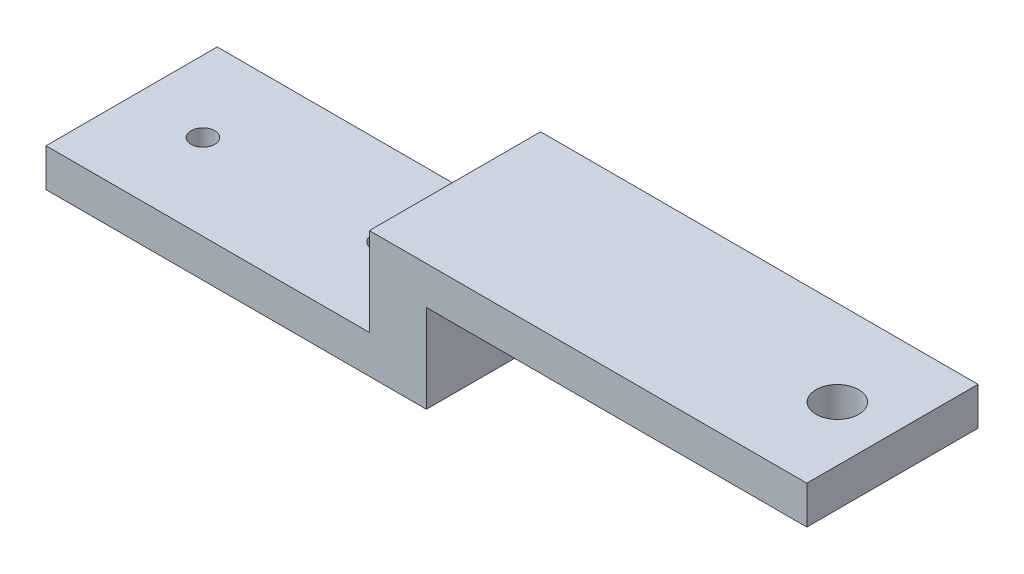
SolidWorks part; units mm, degrees
material "1060 Alloy"
ref_plane "Front Plane" through (0, 0, 0) normal (0, 0, 1) x (1, 0, 0)
ref_plane "Top Plane" through (0, 0, 0) normal (0, 1, 0) x (1, 0, 0)
ref_plane "Right Plane" through (0, 0, 0) normal (1, 0, 0) x (0, 0, -1)
sketch "Sketch1" plane through (0, 0, 0) normal (0, 0, 1) x (1, 0, 0)
  line L0 (-123.8145, -26.5468) -> (-43.8145, -26.5468)
  line L1 (-43.8145, -26.5468) -> (-43.8145, -15.6889)
  line L3 (-29.6039, -8) -> (0.4965, -8)
  line L4 (0.4965, -8) -> (36.1855, -8)
  line L5 (36.1855, -8) -> (36.1855, 0)
  line L6 (36.1855, 0) -> (-33.1894, 0)
  line L9 (-123.8145, -18.5468) -> (-123.8145, -26.5468)
  line L10 (-43.8145, -15.6889) -> (-43.8145, -8)
  line L11 (-43.8145, -8) -> (-29.6039, -8)
  line L14 (-55.8145, 0) -> (-33.1894, 0)
  line L17 (-123.8145, -18.5468) -> (-55.8145, -18.5468)
  line L18 (-55.8145, 0) -> (-55.8145, -18.5468)
  dimension "D1" = 80
  dimension "D2" = 8
  dimension "D3" = 80
  dimension "D4" = 8
  dimension "D5" = 12
  dimension "D6" = 10.5468
extrude "Boss-Extrude1" add sketch "Sketch1" along normal blind 36
sketch "Sketch2" plane through (0, 0, 0) normal (0, 1, 0) x (1, 0, 0)
  line L0 (36.1855, 0) -> (13.0373, -36) construction
  line L1 (36.1855, -36) -> (-55.8145, -36) construction
  line L2 (13.0373, -36) -> (36.1855, -36) construction
  line L3 (36.1855, -36) -> (6.2089, -16.725) construction
  circle A0 centre (24.6114, -18) radius 4.5
  dimension "D1" = 9
extrude "Cut-Extrude1" cut sketch "Sketch2" against normal blind 30
sketch "Sketch3" plane through (0, -18.5468, 0) normal (0, 1, 0) x (1, 0, 0)
  line L0 (-123.8145, -18) -> (-33.7127, -18) construction
  line L1 (-123.8145, -36) -> (-123.8145, 0) construction
  line L2 (-55.8145, -36) -> (-55.8145, 0) construction
  circle A0 centre (-108.8145, -18) radius 2.5
  circle A1 centre (-70.8145, -18) radius 2.5
  dimension "D1" = 5
  dimension "D2" = 5
  dimension "D3" = 15
  dimension "D4" = 15
extrude "Cut-Extrude2" cut sketch "Sketch3" against normal blind 10
